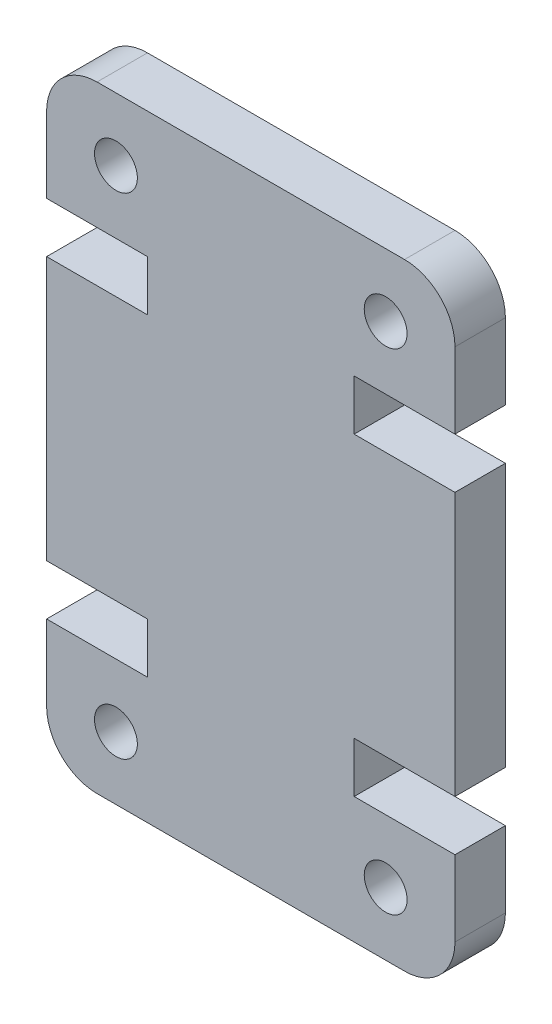
SolidWorks part; units mm, degrees
ref_plane "Front Plane" through (0, 0, 0) normal (0, 0, 1) x (1, 0, 0)
ref_plane "Top Plane" through (0, 0, 0) normal (0, 1, 0) x (1, 0, 0)
ref_plane "Right Plane" through (0, 0, 0) normal (1, 0, 0) x (0, 0, -1)
sketch "Sketch1" plane through (0, 0, 0) normal (0, 0, 1) x (1, 0, 0)
  line L0 (0, 17.45) -> (0, 7)
  line L1 (16.2, 5) -> (16.2, 2)
  line L2 (12.2, 5) -> (16.2, 5)
  line L3 (2, 0) -> (14.2, 0)
  line L4 (16.2, 7) -> (12.2, 7)
  line L5 (12.2, 7) -> (12.2, 5)
  line L6 (16.2, 17.45) -> (16.2, 7)
  line L7 (0, 19.45) -> (0, 22.45)
  line L8 (4, 19.45) -> (0, 19.45)
  line L9 (0, 17.45) -> (4, 17.45)
  line L10 (4, 7) -> (4, 5)
  line L11 (4, 17.45) -> (4, 19.45)
  line L12 (0, 7) -> (4, 7)
  line L13 (4, 5) -> (0, 5)
  line L14 (12.2, 17.45) -> (12.2, 19.45)
  line L15 (16.2, 17.45) -> (12.2, 17.45)
  line L16 (2, 24.45) -> (14.2, 24.45)
  line L17 (12.2, 19.45) -> (16.2, 19.45)
  line L18 (16.2, 19.45) -> (16.2, 22.45)
  line L19 (0, 5) -> (0, 2)
  line L20 (0, 12.225) -> (16.2, 12.225) construction
  line L21 (8.1, 24.45) -> (8.1, 0) construction
  circle A0 centre (13.45, 2.5) radius 0.85
  arc A1 (16.2, 2) -> (14.2, 0) centre (14.2, 2) cw
  circle A2 centre (2.75, 21.95) radius 0.85
  arc A3 (0, 2) -> (2, 0) centre (2, 2) ccw
  arc A4 (0, 22.45) -> (2, 24.45) centre (2, 22.45) cw
  circle A5 centre (2.75, 2.5) radius 0.85
  arc A6 (16.2, 22.45) -> (14.2, 24.45) centre (14.2, 22.45) ccw
  circle A7 centre (13.45, 21.95) radius 0.85
  point P17 (8.1, 12.225)
  dimension "D1" = 1.7
  dimension "D2" = 2
  dimension "D3" = 2.75
  dimension "D4" = 8.1
  dimension "D5" = 2.5
  dimension "D8" = 12.225
  dimension "D6" = 5
extrude "Boss-Extrude1" add sketch "Sketch1" along normal blind 4
sketch "Sketch2" plane through (0, 0, 0) normal (0, 0, -1) x (-1, 0, 0)
  line L0 (0, 0) -> (0, 24.45)
  line L1 (0, 24.45) -> (-16.2, 24.45)
  line L2 (-16.2, 24.45) -> (-16.2, 0)
  line L3 (-16.2, 0) -> (0, 0)
extrude "Cut-Extrude1" cut sketch "Sketch2" against normal blind 2
equation "\"D4@Sketch1\"= \"fingerWidth@parametersSketch@prostheticParameters.SLDPRT\" / 2 'MIP Width"
equation "\"D8@Sketch1\"= ( ( \"HL@parametersSketch@prostheticParameters.SLDPRT\" * 0.17 ) - 4 - 3 ) / 2 'MIP Length - Sil. Sht MIP - Sil. Sht DIP"
equation "\"D1@Sketch1\"= 1.5 + \"tol1@parametersSketch@prostheticParameters.SLDPRT\""
